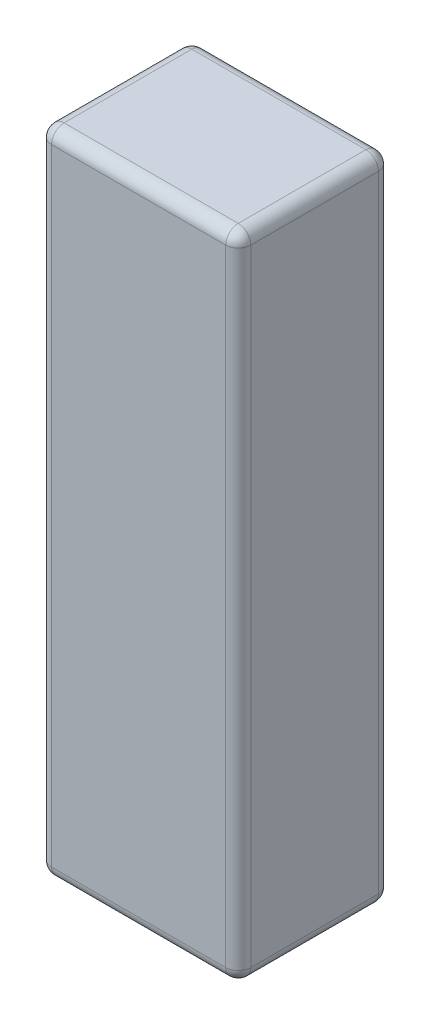
SolidWorks part; units mm, degrees
ref_plane "Front Plane" through (0, 0, 0) normal (0, 0, 1) x (1, 0, 0)
ref_plane "Top Plane" through (0, 0, 0) normal (0, 1, 0) x (1, 0, 0)
ref_plane "Right Plane" through (0, 0, 0) normal (1, 0, 0) x (0, 0, -1)
sketch "Sketch1" plane through (0, 0, 0) normal (0, 0, 1) x (1, 0, 0)
  line L1 (-9.525, -31.115) -> (9.525, -31.115)
  line L2 (-9.525, -31.115) -> (-9.525, 31.115)
  line L3 (-9.525, 31.115) -> (9.525, 31.115)
  line L4 (9.525, -31.115) -> (9.525, 31.115)
  line L5 (-9.525, -31.115) -> (9.525, 31.115) construction
  line L6 (-9.525, 31.115) -> (9.525, -31.115) construction
  point P0 (0, 0)
  dimension "D1" = 62.23
  dimension "D2" = 19.05
extrude "Boss-Extrude1" add sketch "Sketch1" along normal blind 14.605
fillet "Fillet1" radius 1.2 12 edges at (-9.525, 31.115, 7.3025) (-9.525, -31.115, 7.3025) (9.525, -31.115, 7.3025) (9.525, 31.115, 7.3025) (0, 31.115, 0) (-9.525, 0, 0) (0, -31.115, 0) (9.525, 0, 0) (0, -31.115, 14.605) (-9.525, 0, 14.605) (0, 31.115, 14.605) (9.525, 0, 14.605)
